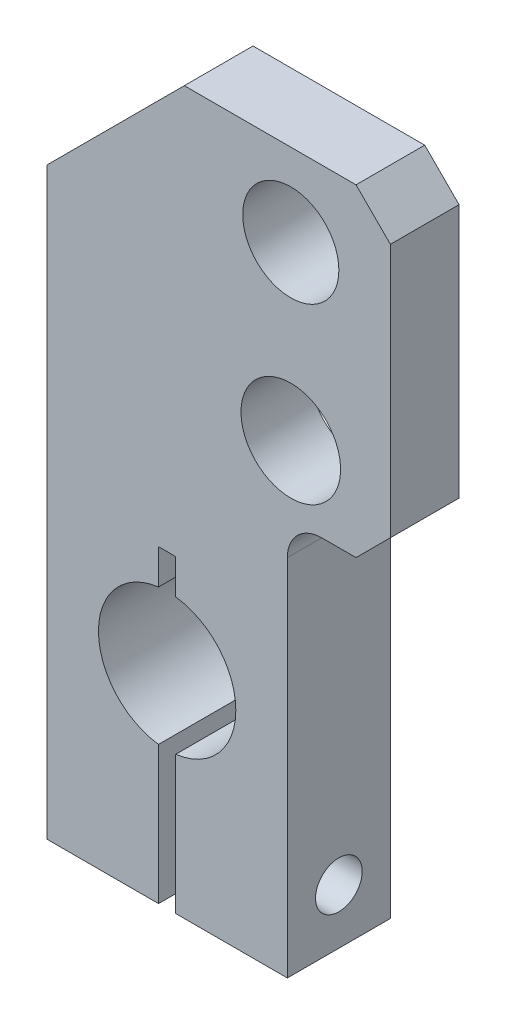
SolidWorks part; units mm, degrees
ref_plane "前视基准面" through (0, 0, 0) normal (0, 0, 1) x (1, 0, 0)
ref_plane "上视基准面" through (0, 0, 0) normal (0, 1, 0) x (1, 0, 0)
ref_plane "右视基准面" through (0, 0, 0) normal (1, 0, 0) x (0, 0, -1)
sketch "草图1" plane through (0, 0, 0) normal (0, 0, 1) x (1, 0, 0)
  line L2 (-17.5, 105) -> (-17.5, 0)
  line L3 (-17.5, 0) -> (17.5, 0)
  line L4 (17.5, 58) -> (17.5, 0)
  line L5 (-17.5, 105) -> (32.5, 105)
  line L6 (32.5, 105) -> (32.5, 58)
  line L7 (32.5, 58) -> (17.5, 58)
  dimension "D1" = 35
  dimension "D2" = 105
  dimension "D3" = 50
  dimension "D4" = 47
extrude "凸台-拉伸1" add sketch "草图1" along normal mid plane 15
sketch "草图2" plane through (0, 0, 7.5) normal (0, 0, 1) x (1, 0, 0)
  line L0 (-17.5, 0) -> (17.5, 0) construction
  circle A0 centre (0, 30) radius 10
  dimension "D2" = 20
  dimension "D1" = 30
extrude "切除-拉伸1" cut sketch "草图2" against normal through all
sketch "草图3" plane through (0, 0, 7.5) normal (0, 0, 1) x (1, 0, 0)
  line L0 (-17.5, 0) -> (17.5, 0) construction
  line L1 (-1.25, 45) -> (1.25, 45)
  line L2 (-1.25, 45) -> (-1.25, 0)
  line L3 (-1.25, 0) -> (1.25, 0)
  line L4 (1.25, 45) -> (1.25, 0)
  line L5 (0, 0) -> (0, 30.1221) construction
  dimension "D1" = 2.5
  dimension "D2" = 45
extrude "切除-拉伸2" cut sketch "草图3" against normal through all
fillet "圆角1" radius 5 1 edges at (17.5, 58, 0)
sketch "草图4" plane through (-17.5, 0, 0) normal (1, 0, 0) x (0, 0, -1)
  line L0 (0, 0) -> (0, 8) construction
  circle A0 centre (0, 8) radius 4.25
  dimension "D2" = 8.5
  dimension "D1" = 8
extrude "切除-拉伸3" cut sketch "草图4" against normal up to surface (16.25 mm away)
hole_wizard "M8x1.25 螺纹孔1" positions "草图6" profile "草图7" tap size "M8x1.25" standard "JIS" end condition through all
sketch "草图6" plane through (17.5, 13.2453, -0.8493) normal (1, 0, 0) x (0, 0, -1)
  point P1 (-0.8493, -5.2453)
sketch "草图7" plane through (17.5, 8, 0) normal (0, 1, 0) x (0, 0, -1)
  line L0 (0, 0) -> (0, 35)
  line L1 (0, 35) -> (3.4, 35)
  line L2 (3.4, 35) -> (3.4, 0)
  line L5 (3.4, 0) -> (0, 0)
  line L11 (0, -6.35) -> (0, 107.95) construction
  dimension "通孔螺纹孔钻头直径" = 6.8
  dimension "通孔螺纹孔钻头深度" = 35
cosmetic thread "孔螺蚊线3" parameters "D1"=16.25, "D2"=8
sketch "草图10" plane through (0, 0, 7.5) normal (0, 0, 1) x (1, 0, 0)
  circle A0 centre (18, 93) radius 7
  arc A1 (1.25, 20.0784) -> (1.25, 39.9216) centre (0, 30) ccw construction
  dimension "D1" = 63
  dimension "D2" = 18
  dimension "D3" = 14
extrude "切除-拉伸4" cut sketch "草图10" against normal through all
sketch "草图11" plane through (0, 0, -7.5) normal (0, 0, -1) x (-1, 0, 0)
  line L1 (-32.5, 105) -> (17.5, 105)
  line L2 (-32.5, 105) -> (-32.5, 55)
  line L3 (-32.5, 55) -> (17.5, 55)
  line L4 (17.5, 105) -> (17.5, 55)
  dimension "D2" = 50
extrude "切除-拉伸5" cut sketch "草图11" against normal blind 5
chamfer "倒角2" distance 5 angle 45 2 edges at (32.5, 105, 2.5) (32.5, 58, 2.5)
chamfer "倒角3" distance 20 angle 45 1 edges at (-17.5, 105, 2.5)
sketch "草图12" plane through (0, 0, -2.5) normal (0, 0, -1) x (-1, 0, 0)
  line L0 (-18, 93) -> (-18, 68) construction
  circle A0 centre (-18, 68) radius 7.25
  circle A1 centre (-18, 93) radius 7 construction
  dimension "D2" = 14.5
  dimension "D1" = 25
extrude "切除-拉伸6" cut sketch "草图12" against normal through all
